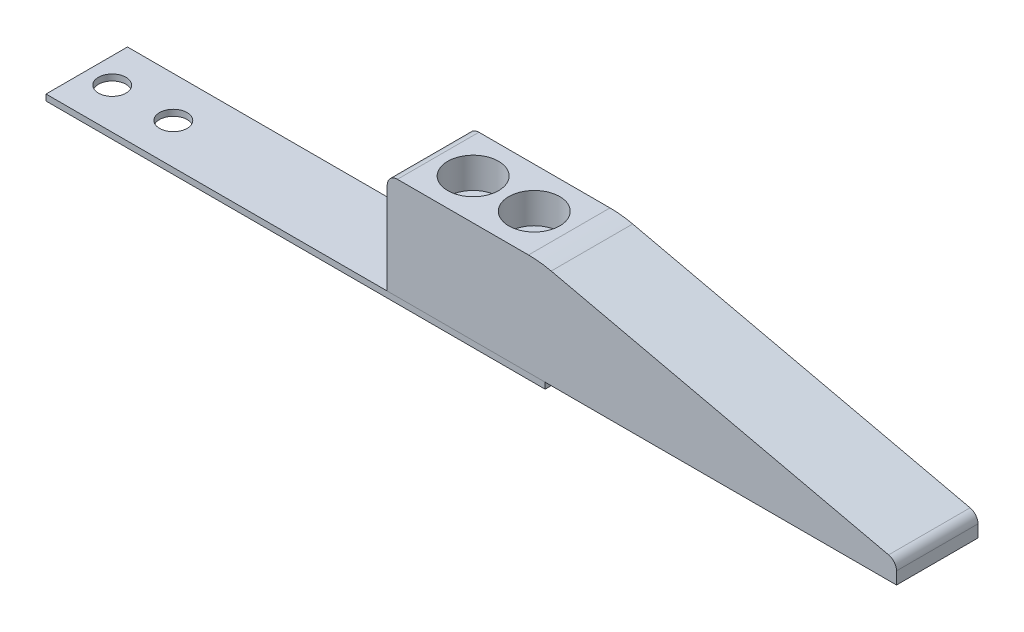
SolidWorks part; units mm, degrees
material "碳纤维"
ref_plane "前视基准面" through (0, 0, 0) normal (0, 0, 1) x (1, 0, 0)
ref_plane "上视基准面" through (0, 0, 0) normal (0, 1, 0) x (1, 0, 0)
ref_plane "右视基准面" through (0, 0, 0) normal (1, 0, 0) x (0, 0, -1)
sketch "草图1" plane through (0, 0, 0) normal (0, 1, 0) x (1, 0, 0)
  line L0 (0, 4) -> (49, 4) construction
  line L1 (0, 0) -> (49, 0)
  line L2 (0, 0) -> (0, 8)
  line L3 (0, 8) -> (49, 8)
  line L4 (49, 0) -> (49, 8)
  circle A0 centre (2.5, 4) radius 1.35
  circle A1 centre (8.5, 4) radius 1.35
  dimension "D3" = 2.7
  dimension "D4" = 2.5
  dimension "D5" = 2.7
  dimension "D6" = 6
  dimension "D1" = 8
  dimension "D2" = 49
extrude "凸台-拉伸1" add sketch "草图1" along normal blind 0.6
sketch "草图2" plane through (0, 0, 0) normal (0, 0, 1) x (1, 0, 0)
  line L0 (33.5, 0.6) -> (33.5, 10.6)
  line L1 (0, 0.6) -> (49, 0.6) construction
  line L2 (0, 0.6) -> (0, 0) construction
  line L3 (33.5, 10.6) -> (48.5, 10.6)
  line L5 (83.5, 0.6) -> (33.5, 0.6)
  line L6 (83.5, 0.6) -> (83.5, 2.6)
  line L7 (83.5, 2.6) -> (48.5, 10.6)
  dimension "D1" = 33.5
  dimension "D2" = 10
  dimension "D3" = 15
  dimension "D4" = 50
  dimension "D5" = 2
extrude "凸台-拉伸2" add sketch "草图2" against normal blind 8 separate body
fillet "圆角1" radius 1 1 edges at (83.5, 2.6, -4)
fillet "圆角2" radius 10 1 edges at (48.5, 10.6, -4)
fillet "圆角3" radius 1 1 edges at (33.5, 10.6, -4)
sketch "草图3" plane through (0, 10.6, 0) normal (0, 1, 0) x (1, 0, 0)
  line L0 (34.5, 4) -> (47.3717, 4) construction
  line L1 (34.5, 8) -> (34.5, 0) construction
  line L2 (47.3717, 0) -> (47.3717, 8) construction
  line L3 (40.9358, 8) -> (40.9358, 0) construction
  line L4 (47.3717, 8) -> (34.5, 8) construction
  line L5 (47.3717, 0) -> (34.5, 0) construction
  circle A0 centre (37.9358, 4) radius 1.35
  circle A1 centre (43.9358, 4) radius 1.35
  dimension "D1" = 2.7
  dimension "D2" = 6
extrude "切除-拉伸1" cut sketch "草图3" against normal through all
sketch "草图4" plane through (0, 10.6, 0) normal (0, 1, 0) x (1, 0, 0)
  circle A0 centre (37.9358, 4) radius 2.5
  circle A1 centre (43.9358, 4) radius 2.5
  dimension "D1" = 5
extrude "切除-拉伸2" cut sketch "草图4" against normal blind 3
